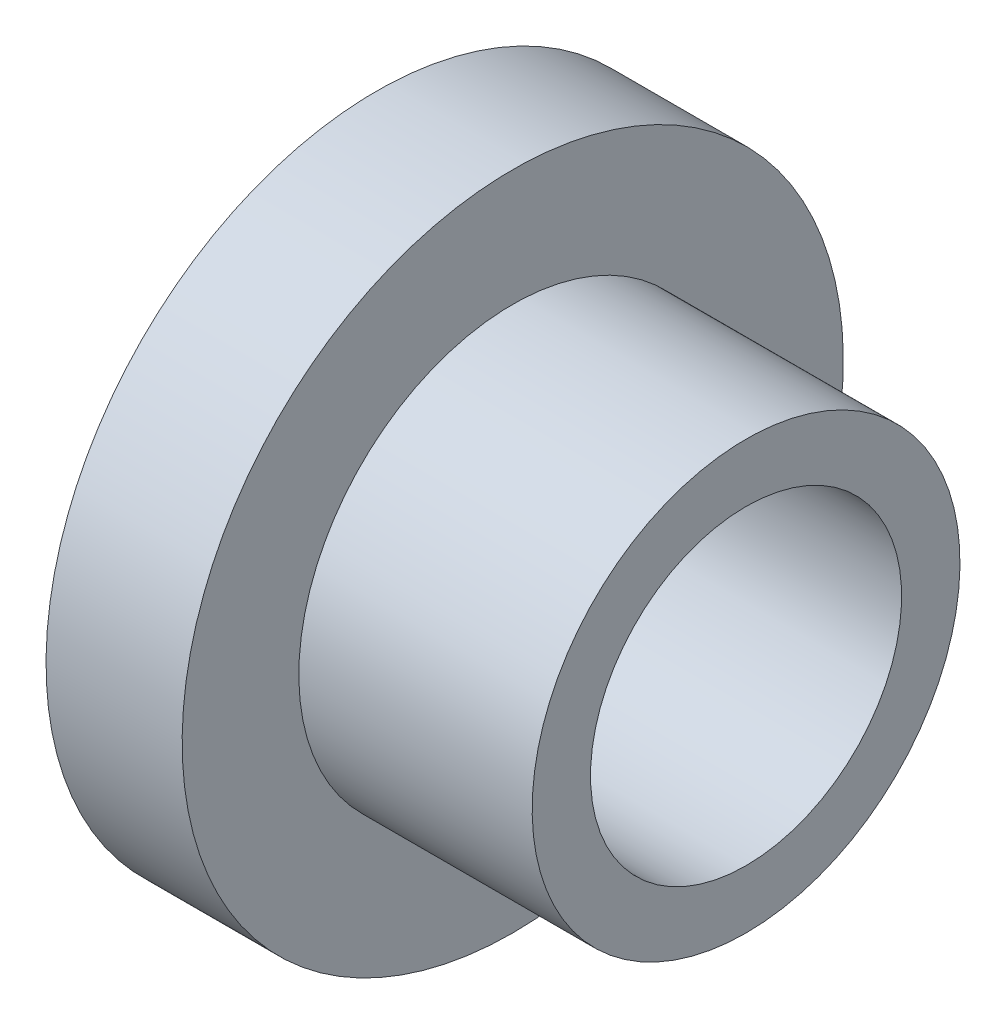
SolidWorks part; units mm, degrees
ref_plane "Plan de face" through (0, 0, 0) normal (0, 0, 1) x (1, 0, 0)
ref_plane "Plan de dessus" through (0, 0, 0) normal (0, 1, 0) x (1, 0, 0)
ref_plane "Plan de droite" through (0, 0, 0) normal (1, 0, 0) x (0, 0, -1)
sketch "Esquisse1" plane through (0, 0, 0) normal (0, 0, 1) x (1, 0, 0)
  line L0 (-12.5, 0) -> (12.5, 0) construction
  line L1 (9.5, -8) -> (9.5, -11)
  line L2 (9.5, -11) -> (-2.5, -11)
  line L3 (-2.5, -11) -> (-2.5, -17)
  line L4 (-2.5, -17) -> (-9.5, -17)
  line L5 (-9.5, -17) -> (-9.5, -8)
  line L6 (-9.5, -8) -> (9.5, -8)
  point P2 (0, 0)
  point P12 (0, -8)
  dimension "D1" = 25
  dimension "D2" = 8
  dimension "D3" = 11
  dimension "D4" = 12
  dimension "D5" = 19
  dimension "D6" = 17
revolve "Révolution1" add sketch "Esquisse1" angle 360 about L0
